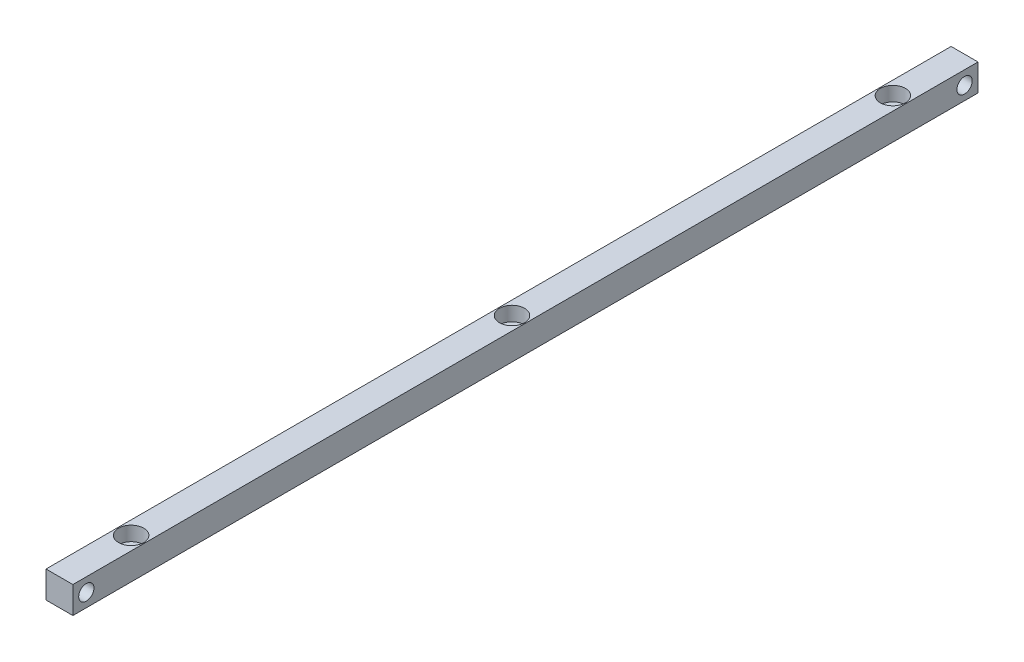
SolidWorks part; units mm, degrees
ref_plane "Ön Düzlem" through (0, 0, 0) normal (0, 0, 1) x (1, 0, 0)
ref_plane "Üst Düzlem" through (0, 0, 0) normal (0, 1, 0) x (1, 0, 0)
ref_plane "Sağ Düzlem" through (0, 0, 0) normal (1, 0, 0) x (0, 0, -1)
sketch "Çizim1" plane through (0, 0, 0) normal (0, 0, 1) x (1, 0, 0)
  line L1 (-7.5, -7.5) -> (7.5, -7.5)
  line L2 (-7.5, -7.5) -> (-7.5, 7.5)
  line L3 (-7.5, 7.5) -> (7.5, 7.5)
  line L4 (7.5, -7.5) -> (7.5, 7.5)
  line L5 (-7.5, -7.5) -> (7.5, 7.5) construction
  line L6 (-7.5, 7.5) -> (7.5, -7.5) construction
  point P0 (0, 0)
  dimension "D1" = 15
extrude "Yükseklik-Ekstrüzyon1" add sketch "Çizim1" along normal mid plane 505
hole_wizard "Delik2" positions "3B Çizim2" profile "Çizim3" legacy
sketch3d "3B Çizim2"
  line L0 (-7.5, 7.5, 252.5) -> (-7.5, -7.5, 252.5) construction
  point P0 (-7.5, 0, 245)
  point P6 (-7.5, 0, 252.5)
  dimension "D1" = 7.5
sketch "Çizim3" plane through (-7.5, 0, 245) normal (0, 1, 0) x (0, 0, 1)
  line L0 (0, 0) -> (0, 15)
  line L1 (0, 15) -> (4.25, 15)
  line L2 (4.25, 15) -> (4.25, 8)
  line L3 (4.25, 8) -> (7, 8)
  line L4 (7, 8) -> (7, 0)
  line L5 (7, 0) -> (0, 0)
  line L6 (0, 110) -> (0, -10) construction
  dimension "Diameter" = 8.5
  dimension "Depth" = 15
  dimension "C-Bore Diameter" = 14
  dimension "C-Bore Depth" = 8
mirror "Aynalama1" about plane through (0, 0, 0) normal (0, 0, 1) of "Delik2"
hole_wizard "Delik3" positions "Çizim6" profile "Çizim7" legacy
sketch "Çizim6" plane through (0, 7.5, 0) normal (0, 1, 0) x (1, 0, 0)
  line L0 (7.5, -252.5) -> (-7.5, -252.5) construction
  point P0 (0, -212.5)
  dimension "D1" = 40
sketch "Çizim7" plane through (0, 7.5, 212.5) normal (1, 0, 0) x (0, 0, 1)
  line L0 (0, 0) -> (0, 15)
  line L1 (0, 15) -> (4.25, 15)
  line L2 (4.25, 15) -> (4.25, 8)
  line L3 (4.25, 8) -> (7, 8)
  line L4 (7, 8) -> (7, 0)
  line L5 (7, 0) -> (0, 0)
  line L6 (0, 110) -> (0, -10) construction
  dimension "Diameter" = 8.5
  dimension "Depth" = 15
  dimension "C-Bore Diameter" = 14
  dimension "C-Bore Depth" = 8
pattern_linear "LÇoğaltma1" count 3 spacing 212.5 along (0, 0, -1) of "Delik3"
